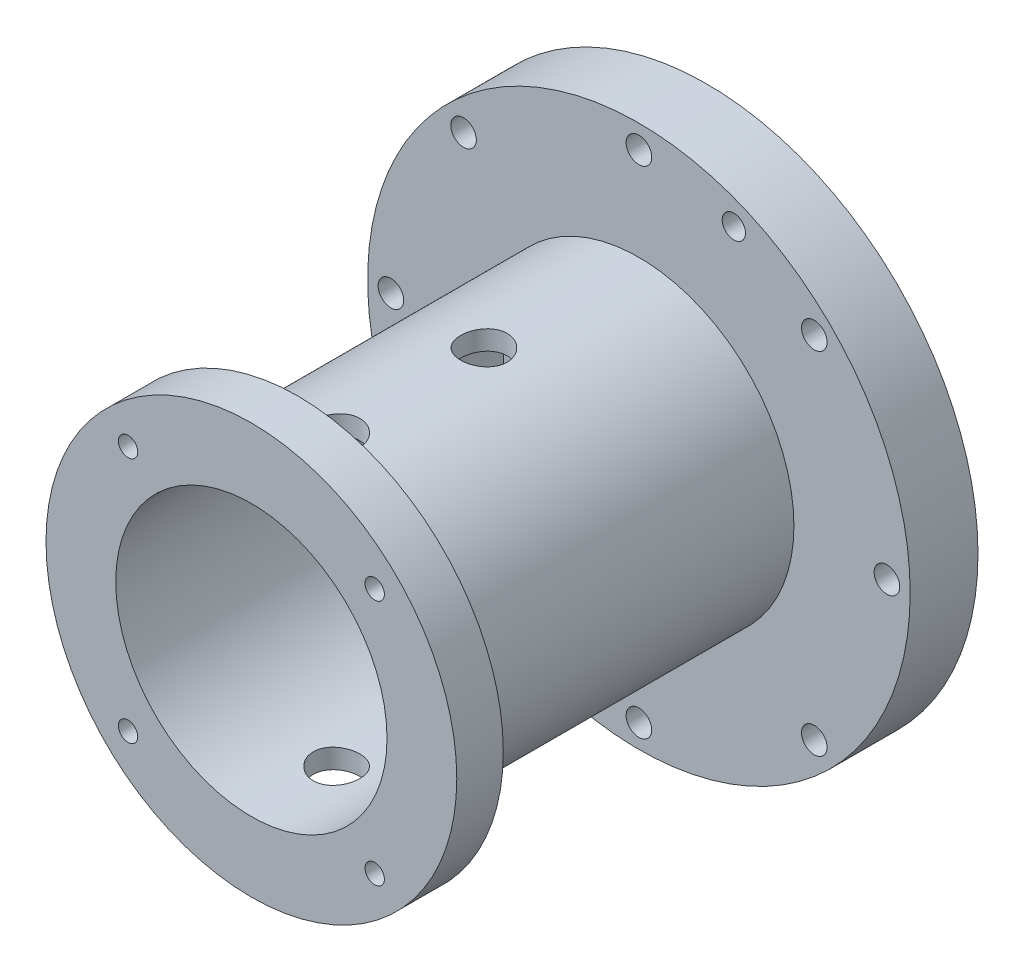
SolidWorks part; units mm, degrees
material "0.7050 (EN-GJS-500-7)"
ref_plane "Front Plane" through (0, 0, 0) normal (0, 0, 1) x (1, 0, 0)
ref_plane "Top Plane" through (0, 0, 0) normal (0, 1, 0) x (1, 0, 0)
ref_plane "Right Plane" through (0, 0, 0) normal (1, 0, 0) x (0, 0, -1)
sketch "Sketch1" plane through (0, 0, 0) normal (0, 1, 0) x (1, 0, 0)
  line L0 (16, -13) -> (22, -13)
  line L1 (22, -13) -> (22, -19)
  line L2 (22, -19) -> (50, -19)
  line L3 (50, -19) -> (50, -7.5)
  line L4 (50, -7.5) -> (70, -7.5)
  line L5 (70, -7.5) -> (70, -25)
  line L6 (70, -25) -> (40, -25)
  line L7 (40, -25) -> (40, -113)
  line L8 (40, -113) -> (53, -113)
  line L9 (53, -113) -> (53, -125)
  line L10 (53, -125) -> (35, -125)
  line L11 (35, -125) -> (35, -25)
  line L12 (35, -25) -> (22, -25)
  line L13 (22, -25) -> (22, -54)
  line L14 (22, -54) -> (16, -54)
  line L15 (16, -54) -> (16, -35)
  line L16 (16, -35) -> (13.5, -35)
  line L17 (13.5, -35) -> (13.5, -25)
  line L18 (13.5, -25) -> (16, -25)
  line L19 (16, -25) -> (16, -13)
  line L20 (0, -150) -> (0, 150) construction
revolve "REV_Input_Housing_Motor_Adapter" add sketch "Sketch1" angle 360 about L20
sketch "Sketch2" plane through (0, 0, 0) normal (0, 0, 1) x (1, 0, 0)
  circle A0 centre (64, 0) radius 3.3
  circle A1 centre (45.2548, 45.2548) radius 3.3
  circle A2 centre (0, 64) radius 3.3
  circle A3 centre (-45.2548, 45.2548) radius 3.3
  circle A4 centre (-64, 0) radius 3.3
  circle A5 centre (-45.2548, -45.2548) radius 3.3
  circle A6 centre (0, -64) radius 3.3
  circle A7 centre (45.2548, -45.2548) radius 3.3
  circle A8 centre (24.4917, 59.1283) radius 3
  circle A9 centre (-24.4917, -59.1283) radius 3
extrude "CUT_8xTie_D6.6_2xDowel_D6_PCD128" cut sketch "Sketch2" along normal mid plane 300
sketch "Sketch3" plane through (0, 0, 125) normal (0, 0, 1) x (1, 0, 0)
  circle A0 centre (31.8198, 31.8198) radius 2.5
  circle A1 centre (-31.8198, 31.8198) radius 2.5
  circle A2 centre (-31.8198, -31.8198) radius 2.5
  circle A3 centre (31.8198, -31.8198) radius 2.5
extrude "CUT_4xM6_Motor_Taps_PCD90" cut sketch "Sketch3" against normal blind 12
sketch "Sketch4" plane through (0, 0, 0) normal (0, 1, 0) x (1, 0, 0)
  circle A0 centre (0, -65) radius 6
  circle A1 centre (0, -103) radius 6
extrude "CUT_Coupling_Access_D12" cut sketch "Sketch4" along normal mid plane 300
